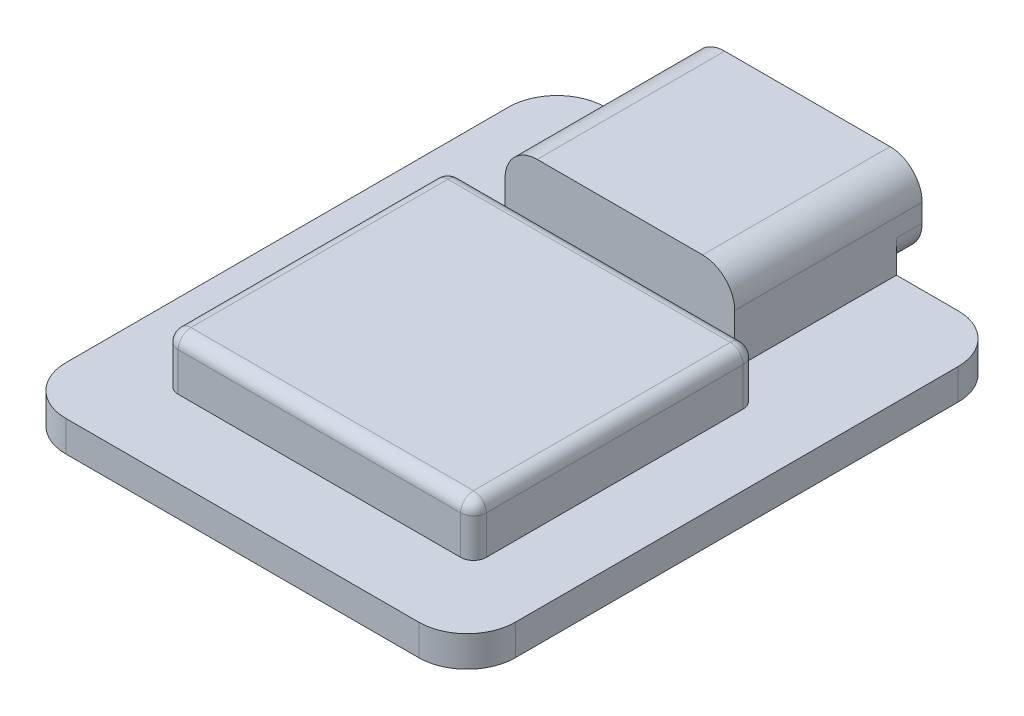
SolidWorks part; units mm, degrees
ref_plane "Front Plane" through (0, 0, 0) normal (0, 0, 1) x (1, 0, 0)
ref_plane "Top Plane" through (0, 0, 0) normal (0, 1, 0) x (1, 0, 0)
ref_plane "Right Plane" through (0, 0, 0) normal (1, 0, 0) x (0, 0, -1)
sketch "Sketch1" plane through (0, 0, 0) normal (0, 1, 0) x (1, 0, 0)
  line L0 (-8.75, 10.5) -> (8.75, -10.5) construction
  line L1 (-8.75, 10.5) -> (8.75, 10.5)
  line L2 (-8.75, 10.5) -> (-8.75, -10.5)
  line L3 (-8.75, -10.5) -> (8.75, -10.5)
  line L4 (8.75, 10.5) -> (8.75, -10.5)
  point P4 (0, 0)
  dimension "D1" = 17.5
  dimension "D2" = 21
extrude "Boss-Extrude1" add sketch "Sketch1" along normal blind 1.2
fillet "Fillet1" radius 1.88 4 edges at (8.75, 0.6, -10.5) (-8.75, 0.6, -10.5) (-8.75, 0.6, 10.5) (8.75, 0.6, 10.5)
sketch "Sketch2" plane through (0, 1.2, 0) normal (0, 1, 0) x (1, 0, 0)
  line L0 (-6.87, -10.5) -> (6.87, -10.5) construction
  line L1 (-6, 3.5) -> (6, 3.5)
  line L2 (-6, 3.5) -> (-6, -7.5)
  line L3 (-6, -7.5) -> (6, -7.5)
  line L4 (6, 3.5) -> (6, -7.5)
  point P4 (0, -7.5)
  dimension "D1" = 12
  dimension "D2" = 11
  dimension "D3" = 3
extrude "Boss-Extrude2" add sketch "Sketch2" along normal blind 2
fillet "Fillet2" radius 0.5 8 edges at (0, 3.2, -3.5) (6, 3.2, 2) (0, 3.2, 7.5) (-6, 3.2, 2) (-6, 2.2, -3.5) (-6, 2.2, 7.5) (6, 2.2, -3.5) (6, 2.2, 7.5)
sketch "Sketch3" plane through (0, 1.2, 0) normal (0, 1, 0) x (1, 0, 0)
  line L0 (6.87, 10.5) -> (-6.87, 10.5) construction
  line L1 (-4.47, 11.5) -> (4.47, 11.5)
  line L2 (-4.47, 11.5) -> (-4.47, 4.2)
  line L3 (-4.47, 4.2) -> (4.47, 4.2)
  line L4 (4.47, 11.5) -> (4.47, 4.2)
  point P6 (0, 11.5)
  dimension "D1" = 8.94
  dimension "D2" = 6.3
  dimension "D3" = 1
extrude "Boss-Extrude3" add sketch "Sketch3" along normal blind 3.21
fillet "Fillet3" radius 1.25 4 edges at (-4.47, 1.2, -11) (-4.47, 4.41, -7.85) (4.47, 1.2, -11) (4.47, 4.41, -7.85)
sketch "Sketch4" plane through (0, 0, -11.5) normal (0, 0, -1) x (-1, 0, 0)
  line L0 (-3.25, 2.805) -> (3.25, 2.805) construction
  line L1 (-3.25, 3.805) -> (3.25, 3.805)
  line L2 (-3.25, 1.805) -> (3.25, 1.805)
  line L3 (-4.47, 3.16) -> (-4.47, 2.45) construction
  line L4 (-2.5, 2.805) -> (2.5, 2.805) construction
  line L5 (-2.5, 3.305) -> (2.5, 3.305)
  line L6 (-2.5, 2.305) -> (2.5, 2.305)
  arc A0 (-3.25, 3.805) -> (-3.25, 1.805) centre (-3.25, 2.805) ccw
  arc A1 (3.25, 1.805) -> (3.25, 3.805) centre (3.25, 2.805) ccw
  arc A2 (-2.5, 3.305) -> (-2.5, 2.305) centre (-2.5, 2.805) ccw
  arc A3 (2.5, 2.305) -> (2.5, 3.305) centre (2.5, 2.805) ccw
  point P2 (0, 2.805)
  point P9 (-4.47, 2.805)
  point P12 (0, 2.805)
  dimension "D2" = 1
  dimension "D4" = 0.5
  dimension "D1" = 6.5
  dimension "D3" = 5
extrude "Cut-Extrude1" cut sketch "Sketch4" against normal blind 5
